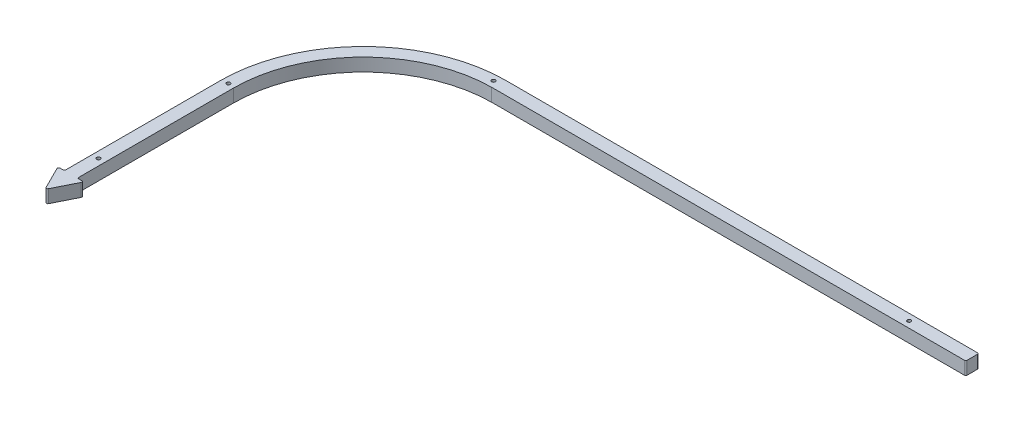
SolidWorks part; units mm, degrees
material "Acrylic (Medium-high impact)"
ref_plane "Front" through (0, 0, 0) normal (0, 0, 1) x (1, 0, 0)
ref_plane "Top" through (0, 0, 0) normal (0, 1, 0) x (1, 0, 0)
ref_plane "Right" through (0, 0, 0) normal (1, 0, 0) x (0, 0, -1)
sketch "Sketch1" plane through (0, 0, 0) normal (0, 1, 0) x (1, 0, 0)
  line L0 (69.0717, 158.7457) -> (69.0717, 152.3952)
  line L1 (0, 0) -> (6.35, 0)
  line L2 (0, 0) -> (0, 88.9)
  line L3 (0, 88.9) -> (6.35, 88.9)
  line L4 (6.35, 0) -> (6.35, 88.9)
  line L9 (69.0717, 158.7457) -> (300.8467, 158.7457)
  line L10 (69.0717, 152.3952) -> (300.8467, 152.3952)
  line L11 (300.8467, 158.7457) -> (300.8467, 152.3952)
  line L19 (9.525, 0) -> (-3.175, 0)
  line L20 (9.525, 0) -> (9.525, 12.7)
  line L21 (9.525, 12.7) -> (-3.175, 12.7)
  line L22 (-3.175, 0) -> (-3.175, 12.7)
  arc A0 (6.35, 88.9) -> (69.0717, 152.3952) centre (69.85, 88.9) cw
  arc A1 (0, 88.9) -> (69.0717, 158.7457) centre (69.85, 88.9) cw
  point P14 (3.175, 0)
  dimension "D1" = 6.35
  dimension "D2" = 88.9
  dimension "D3" = 231.775
  dimension "D4" = 63.5
  dimension "D5" = 12.7
  dimension "D6" = 12.7
  dimension "D7" = 12.7
  dimension "D8" = 6.35
extrude "Boss-Extrude1" add sketch "Sketch1" along normal blind 6.35 contours L1 L4 L3 L2 | A1 L3 A0 L0 | L11 L9 L0 L10
sketch "Sketch2" plane through (0, 6.35, 0) normal (0, 1, 0) x (1, 0, 0)
  line L0 (-3.175, 12.7) -> (3.175, 0)
  line L1 (9.525, 0) -> (-3.175, 0) construction
  line L2 (3.175, 0) -> (9.525, 12.7)
  line L3 (-3.175, 12.7) -> (9.525, 12.7)
  line L4 (9.525, 12.7) -> (9.525, 0)
  line L5 (9.525, 0) -> (-3.175, 0)
  line L6 (-3.175, 0) -> (-3.175, 12.7) construction
  line L7 (-3.175, 0) -> (-3.175, 12.7)
  line M3 (-3.175, 12.7) -> (-3.175, 0)
  line M4 (-3.175, 0) -> (9.525, 0)
  line M5 (9.525, 0) -> (9.525, 12.7)
extrude "Cut-Extrude1" cut sketch "Sketch2" against normal through all contours L0 M3 M4 | L2 M4 M5
fillet "Fillet1" radius 0.635 7 edges at (300.8467, 3.175, -158.7457) (300.8467, 3.175, -152.3952) (6.35, 3.175, -12.7) (0, 3.175, -12.7) (-3.175, 3.175, -12.7) (9.525, 3.175, -12.7) (3.175, 3.175, 0)
sketch "Sketch3" plane through (0, 6.35, 0) normal (0, 1, 0) x (1, 0, 0)
  line L0 (3.175, 0.7849) -> (3.175, 97.5392) construction
  line L1 (300.8467, 155.5704) -> (63.5774, 155.5704) construction
  line L2 (300.8467, 158.1107) -> (300.8467, 153.0302) construction
  arc A0 (2.607, 1.1359) -> (3.743, 1.1359) centre (3.175, 1.4199) ccw construction
  circle A1 centre (3.175, 26.1849) radius 0.889
  circle A2 centre (3.175, 89.6849) radius 0.889
  circle A3 centre (66.802, 155.5704) radius 0.889
  circle A4 centre (270.002, 155.5704) radius 0.889
  dimension "D1" = 1.778
  dimension "D4" = 1.778
  dimension "D5" = 63.627
  dimension "D2" = 25.4
  dimension "D3" = 2
  dimension "D6" = 2
extrude "Cut-Extrude2" cut sketch "Sketch3" against normal through all
